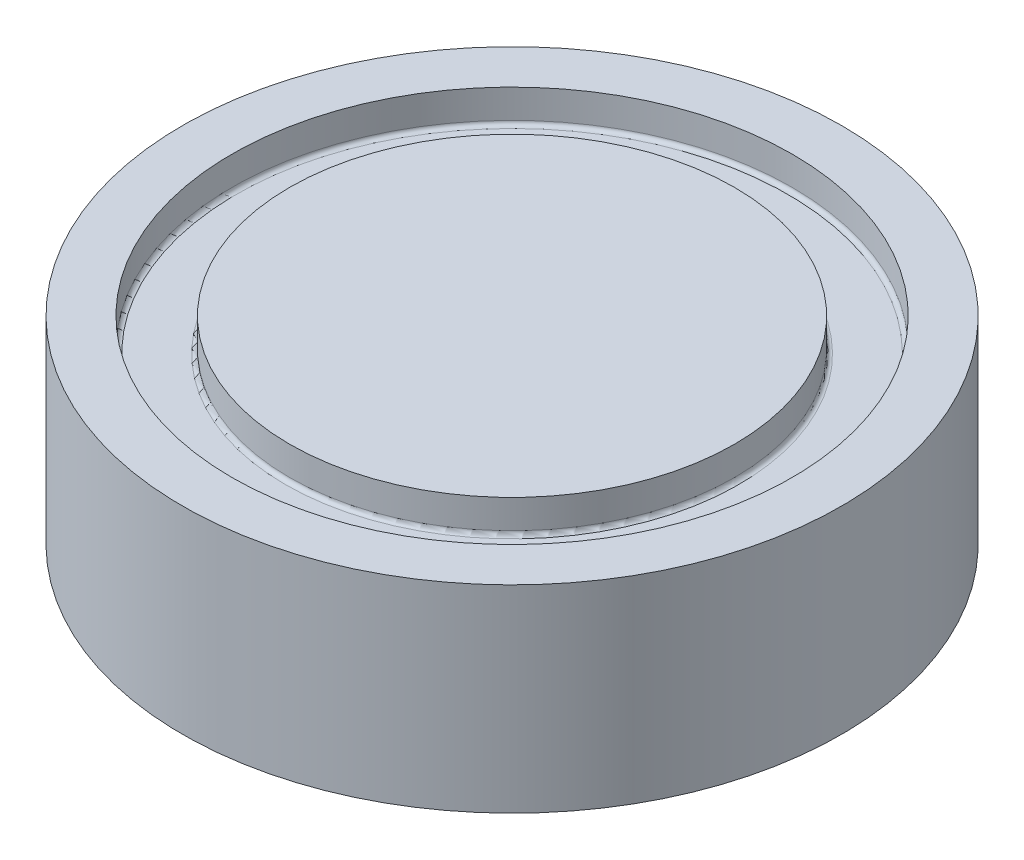
SolidWorks part; units mm, degrees
ref_plane "Front Plane" through (0, 0, 0) normal (0, 0, 1) x (1, 0, 0)
ref_plane "Top Plane" through (0, 0, 0) normal (0, 1, 0) x (1, 0, 0)
ref_plane "Right Plane" through (0, 0, 0) normal (1, 0, 0) x (0, 0, -1)
sketch "Sketch1" plane through (0, 0, 0) normal (0, 1, 0) x (1, 0, 0)
  circle A0 centre (0, 0) radius 50.8
extrude "Boss-Extrude1" add sketch "Sketch1" along normal blind 30.48
hole_wizard "1-14 Tapped Hole1" positions "Sketch2" profile "Sketch3" tap size "1-14" standard "ANSI Inch"
sketch "Sketch2" plane through (0, 0, 0) normal (0, -1, 0) x (-1, 0, 0)
  point P0 (0, 0)
sketch "Sketch3" plane through (0, 0, 0) normal (1, 0, 0) x (0, 0, -1)
  line L0 (0, 0) -> (0, 22.394)
  line L1 (0, 22.394) -> (11.9062, 15.24)
  line L2 (11.9062, 15.24) -> (11.9062, 0)
  line L5 (11.9062, 0) -> (0, 0)
  line L10 (0, 22.394) -> (-11.9063, 15.24) construction
  line L11 (0, -6.35) -> (0, 107.95) construction
  dimension "Tap Drill Dia." = 23.8125
  dimension "Tap Drill Depth" = 15.24
  dimension "Drill Angle" = 118
cosmetic thread "Hole Thread1" parameters "D1"=12.7, "D2"=25.4
sketch "Sketch4" plane through (0, 30.48, 0) normal (0, 1, 0) x (1, 0, 0)
  circle A0 centre (0, 0) radius 34.29
  circle A1 centre (0, 0) radius 43.18
  dimension "D1" = 68.58
  dimension "D2" = 86.36
extrude "Cut-Extrude1" cut sketch "Sketch4" against normal blind 5.08
fillet "Fillet1" radius 0.635 2 edges at (0, 25.4, 43.18) (0, 25.4, 34.29)
